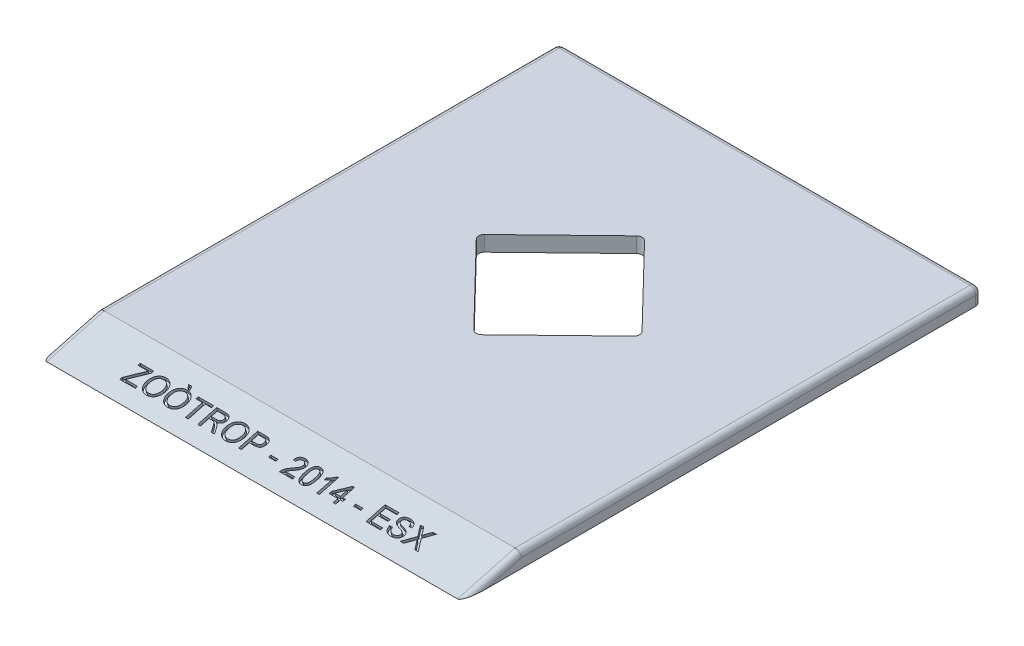
SolidWorks part; units mm, degrees
ref_plane "Alzado" through (0, 0, 0) normal (0, 0, 1) x (1, 0, 0)
ref_plane "Planta" through (0, 0, 0) normal (0, 1, 0) x (1, 0, 0)
ref_plane "Vista lateral" through (0, 0, 0) normal (1, 0, 0) x (0, 0, -1)
sketch "Croquis1" plane through (0, 0, 0) normal (0, 1, 0) x (1, 0, 0)
  line L1 (-55, 55) -> (55, 55) construction
  line L2 (-55, 55) -> (-55, -80) construction
  line L3 (-55, -80) -> (55, -80) construction
  line L4 (55, 55) -> (55, -80) construction
  circle A0 centre (0, 0) radius 50 construction
  dimension "D1" = 100
  dimension "D2" = 55
  dimension "D3" = 55
  dimension "D4" = 135
  dimension "D5" = 110
sketch "Croquis2" plane through (0, 0, 0) normal (1, 0, 0) x (0, 0, -1)
  line L0 (55, 0) -> (-80, 0)
  line L3 (-80, 0) -> (-65, 4)
  line L4 (-65, 4) -> (55, 4)
  line L5 (55, 4) -> (55, 0)
  dimension "D1" = 120
  dimension "D2" = 55
  dimension "D3" = 4
  dimension "D4" = 135
extrude "Saliente-Extruir1" add sketch "Croquis2" along normal mid plane 110
sketch "Croquis3" plane through (0, 19.917, 5.3112) normal (0, 0.9662, 0.2577) x (1, 0, 0)
  line L0 (-55, -72.7746) -> (55, -72.7746) construction
  line L1 (-55, 53.1429) -> (-55, -77.2988) construction
  line L2 (55, 53.1429) -> (55, -77.2988) construction
  line L4 (55, -61.7746) -> (-55, -61.7746) construction
  text T0 "ZOÒTROP - 2014 - ESX" font "Arial" height in points 20
  dimension "D1" = 11
extrude "Cortar-Extruir1" cut sketch "Croquis3" against normal blind 0.8
sketch "Croquis4" plane through (0, 4, 0) normal (0, 1, 0) x (1, 0, 0)
  line L0 (0, 22.2767) -> (-22.2654, 0.707)
  line L1 (0, 22.2767) -> (22.2654, -0.707)
  line L2 (-22.2654, 0.707) -> (0, -22.2767)
  line L3 (22.2654, -0.707) -> (0, -22.2767)
  line L4 (-22.2654, 0.707) -> (22.2654, -0.707) construction
  line L5 (0, 22.2767) -> (0, -22.2767) construction
  dimension "D1" = 31
  dimension "D2" = 32
extrude "Cortar-Extruir2" cut sketch "Croquis4" against normal blind 21
fillet "Redondeo1" radius 1.5 4 edges at (0, 2, 22.2767) (22.2654, 2, 0.707) (-22.2654, 2, -0.707) (0, 2, -22.2767)
fillet "Redondeo2" radius 1.5 7 edges at (0, 4, -55) (55, 4, 5) (55, 2, 72.5) (-55, 2, 72.5) (-55, 4, 5) (-55, 2, -55) (55, 2, -55)
